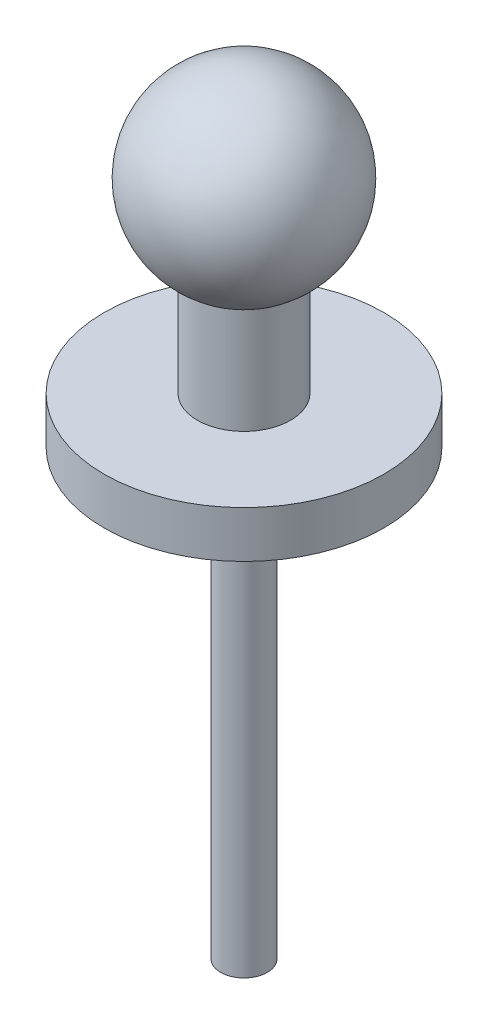
SolidWorks part; units mm, degrees
ref_plane "Front Plane" through (0, 0, 0) normal (0, 0, 1) x (1, 0, 0)
ref_plane "Top Plane" through (0, 0, 0) normal (0, 1, 0) x (1, 0, 0)
ref_plane "Right Plane" through (0, 0, 0) normal (1, 0, 0) x (0, 0, -1)
ref_plane "Plane1" through (0, 5, 0) normal (0, 1, 0) x (1, 0, 0)
ref_plane "Plane2" through (0, 53, 0) normal (0, 1, 0) x (1, 0, 0)
sketch "Sketch6" plane through (0, 53, 0) normal (0, 1, 0) x (1, 0, 0)
  line L0 (-4, 0) -> (4, 0) construction
  line L1 (-4, 0) -> (4, 0)
  arc A0 (-4, 0) -> (4, 0) centre (0, 0) cw
  point P3 (0, 0)
  dimension "D1" = 8
ref_plane "Plane3" through (0, 24, 0) normal (0, 1, 0) x (1, 0, 0)
ref_plane "Plane4" through (0, 45, 0) normal (0, 1, 0) x (1, 0, 0)
sketch "Sketch7" plane through (0, 24, 0) normal (0, 1, 0) x (1, 0, 0)
  circle A0 centre (0, 0) radius 1
  dimension "D1" = 2
extrude "Boss-Extrude1" add sketch "Sketch7" along normal blind 19
sketch "Sketch8" plane through (0, 43, 0) normal (0, 1, 0) x (1, 0, 0)
  line L0 (-4, 0) -> (4, 0) construction
  circle A0 centre (0, 0) radius 6
  dimension "D1" = 12
extrude "Boss-Extrude2" add sketch "Sketch8" along normal blind 2 contours A0
sketch "Sketch9" plane through (0, 45, 0) normal (0, 1, 0) x (1, 0, 0)
  circle A0 centre (0, 0) radius 2
  dimension "D1" = 4
extrude "Boss-Extrude3" add sketch "Sketch9" along normal blind 5
revolve "Revolve1" add sketch "Sketch6" angle 360 about L0
